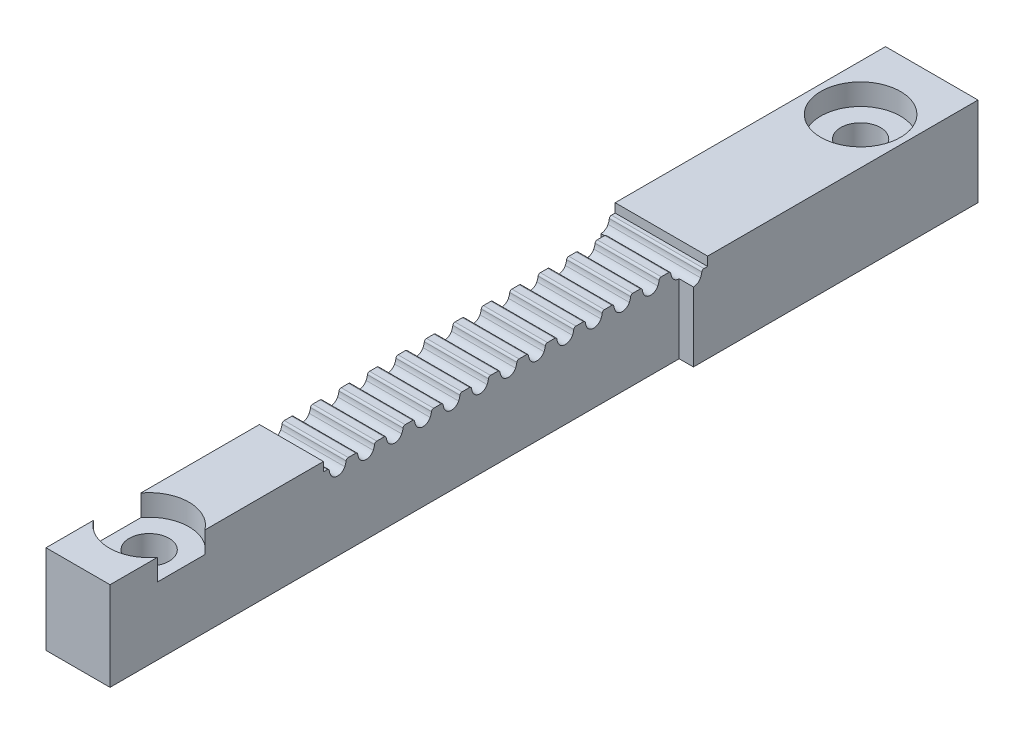
SolidWorks part; units mm, degrees
ref_plane "Front Plane" through (0, 0, 0) normal (0, 0, 1) x (1, 0, 0)
ref_plane "Top Plane" through (0, 0, 0) normal (0, 1, 0) x (1, 0, 0)
ref_plane "Right Plane" through (0, 0, 0) normal (1, 0, 0) x (0, 0, -1)
sketch "Sketch1" plane through (0, 0, 0) normal (0, 1, 0) x (1, 0, 0)
  line L1 (0, 0) -> (6.5, 0)
  line L2 (0, 0) -> (0, 60)
  line L3 (0, 60) -> (6.5, 60)
  line L4 (6.5, 0) -> (6.5, 60)
  dimension "D1" = 6.5
  dimension "D2" = 60
extrude "Boss-Extrude1" add sketch "Sketch1" along normal blind 6.25
sketch "Sketch9" plane through (0, 0, 0) normal (-1, 0, 0) x (0, 0, 1)
  line L0 (-19, 6.25) -> (-15, 6.25)
  line L1 (-17.2598, 5.62) -> (-16.7402, 5.62)
  line L2 (-16, 4.87) -> (-16, 7.2354) construction
  line L3 (-15, 5.62) -> (-15.2598, 5.62)
  line L4 (-19.2899, 5.874) -> (-14.9557, 5.874) construction
  line L5 (-15.6, 6.2736) -> (-15.6, 6.6221) construction
  line L6 (-17, 7.2354) -> (-17, 5.5635) construction
  line L7 (-19, 5.62) -> (-18.7402, 5.62)
  line L8 (-20.5864, 4.87) -> (-16.2522, 4.87) construction
  line L9 (-19, 5.62) -> (-19, 6.25)
  line L10 (-15, 6.25) -> (-15, 5.62)
  line L12 (-60, 6.25) -> (0, 6.25) construction
  line L13 (0, 6.25) -> (0, 0) construction
  arc A0 (-16.4989, 5.1818) -> (-15.5011, 5.1818) centre (-16, 5.425) ccw
  arc A1 (-16.5915, 5.4896) -> (-16.4989, 5.1818) centre (-15.6, 5.62) ccw
  arc A2 (-16.5915, 5.4896) -> (-16.7402, 5.62) centre (-16.7402, 5.47) ccw
  arc A3 (-15.4085, 5.4896) -> (-15.2598, 5.62) centre (-15.2598, 5.47) cw
  arc A4 (-15.4085, 5.4896) -> (-15.5011, 5.1818) centre (-16.4, 5.62) cw
  arc A5 (-17.4085, 5.4896) -> (-17.2598, 5.62) centre (-17.2598, 5.47) cw
  arc A6 (-17.4085, 5.4896) -> (-17.5011, 5.1818) centre (-18.4, 5.62) cw
  arc A7 (-18.5915, 5.4896) -> (-18.7402, 5.62) centre (-18.7402, 5.47) ccw
  arc A8 (-18.5915, 5.4896) -> (-18.4989, 5.1818) centre (-17.6, 5.62) ccw
  arc A9 (-17.5011, 5.1818) -> (-18.4989, 5.1818) centre (-18, 5.425) cw
  point P24 (-17, 5.62)
  dimension "D8" = 0.15
  dimension "D9" = 1
  dimension "D10" = 0.555
  dimension "D11" = 0.2899
  dimension "D1" = 0.63
  dimension "D2" = 4
  dimension "D3" = 4.3342
  dimension "D4" = 4.3342
  dimension "D5" = 0.2598
  dimension "D6" = 1.6719
  dimension "D7" = 2.3654
  dimension "D12" = 1.6154
  dimension "D13" = 0.3485
  dimension "D14" = 0.0236
  dimension "D15" = 0.195
  dimension "D16" = 0.376
  dimension "D17" = 15
extrude "Cut-Extrude3" cut sketch "Sketch9" against normal through all
pattern_linear "LPattern1" count 12 spacing 2 along (0, 0, -1) of "Cut-Extrude3"
sketch "Sketch7" plane through (0, 0, 0) normal (-1, 0, 0) x (0, 0, 1)
  line L0 (-30, 0) -> (-30, 6.25) construction
  line L1 (-60, 0) -> (0, 0) construction
  line L2 (-60, 6.25) -> (-41, 6.25) construction
hole_wizard "CBORE for M1.6 SHCS1" positions "Sketch4" profile "Sketch5" counterbore size "M1.6" standard "ANSI Metric" end condition through all
sketch "Sketch4" plane through (0, 6.25, 0) normal (0, 1, 0) x (1, 0, 0)
  line L2 (6.5, 41) -> (6.5, 60) construction
  line L4 (0, 55) -> (6.5, 55) construction
  line L11 (0, 0) -> (6.5, 0) construction
  line L12 (3.25, 5) -> (6.5, 5) construction
  line L15 (6.5, 5) -> (3.25, 5) construction
  line L16 (3.25, 5) -> (0, 5) construction
  line L19 (6.5, 0) -> (6.5, 15) construction
  line L20 (0, 15) -> (0, 0) construction
  line L23 (6.5, 60) -> (0, 60) construction
  point P2 (3.25, 55)
  point P17 (3.25, 55)
  point P29 (3.25, 5)
  dimension "D1" = 5
  dimension "D3" = 5
sketch "Sketch5" plane through (3.25, 6.25, -55) normal (1, 0, 0) x (0, 0, 1)
  line L0 (0, 0) -> (0, 6.25)
  line L1 (0, 6.25) -> (1.4, 6.25)
  line L3 (1.4, 6.25) -> (1.4, 1.5)
  line L4 (1.4, 1.5) -> (2.8, 1.5)
  line L5 (2.8, 1.5) -> (2.8, 0)
  line L7 (2.8, 0) -> (0, 0)
  line L11 (0, -6.35) -> (0, 32.2439) construction
  dimension "Thru Hole Dia." = 2.8
  dimension "Thru Hole Depth" = 6.25
  dimension "C'Bore Dia." = 5.6
  dimension "C'Bore Depth" = 1.5
sketch "Sketch6" plane through (0, 6.25, 0) normal (0, 1, 0) x (1, 0, 0)
  line L0 (0, 0) -> (6.5, 0) construction
  line L1 (6.5, 40) -> (5.5, 40)
  line L2 (6.5, 40) -> (6.5, 0)
  line L3 (6.5, 0) -> (5.5, 0)
  line L4 (5.5, 40) -> (5.5, 0)
  line L6 (0, 0) -> (1, 0)
  line L7 (0, 0) -> (0, 40)
  line L8 (0, 40) -> (1, 40)
  line L9 (1, 0) -> (1, 40)
  line L10 (0, 15) -> (0, 0) construction
  line L12 (6.5, 41) -> (6.5, 60) construction
  dimension "D1" = 1
  dimension "D3" = 40
extrude "Cut-Extrude2" cut sketch "Sketch6" against normal through all
